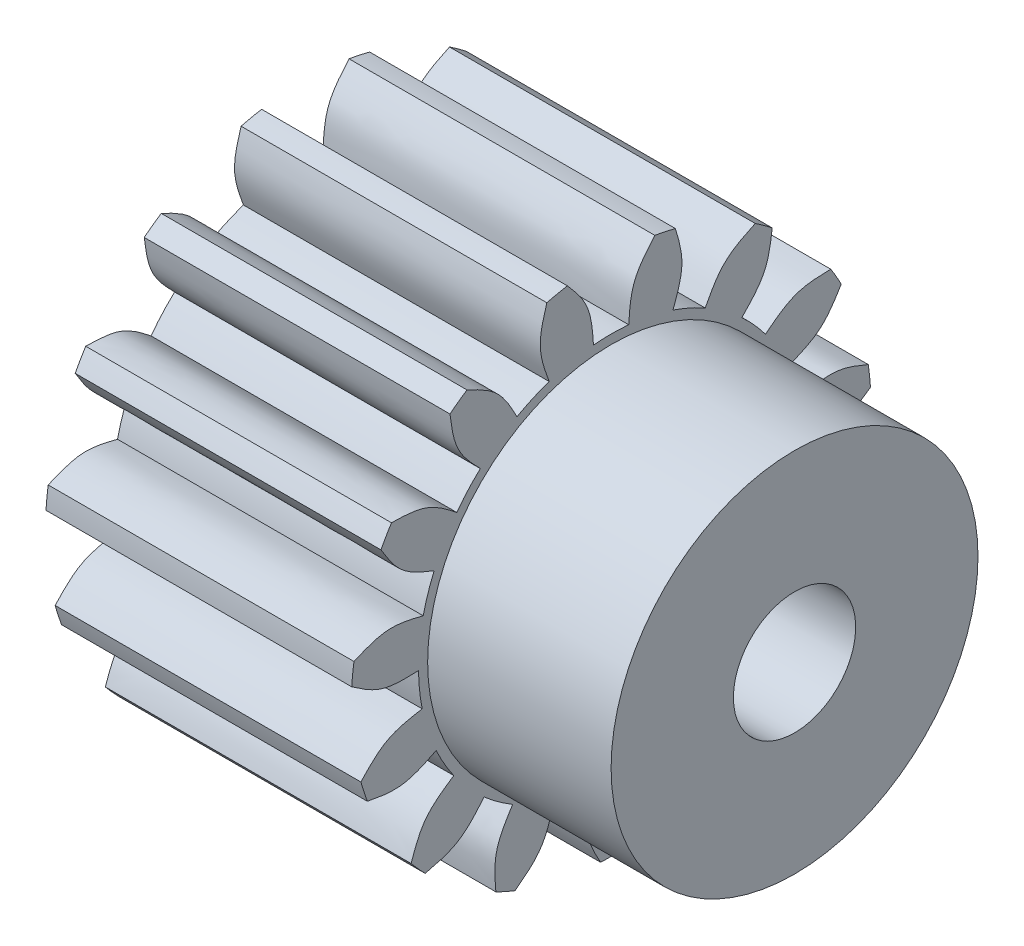
SolidWorks part; units mm, degrees
ref_plane "Front" through (0, 0, 0) normal (0, 0, 1) x (1, 0, 0)
ref_plane "Top" through (0, 0, 0) normal (0, 1, 0) x (1, 0, 0)
ref_plane "Right" through (0, 0, 0) normal (1, 0, 0) x (0, 0, -1)
sketch "Ritning 1" plane through (0, 0, 0) normal (0, 0, 1) x (1, 0, 0)
  line L0 (-20, -10.625) -> (20, -10.625) construction
  line L1 (-20, -5.625) -> (20, -5.625)
  line L2 (20, -5.625) -> (20, 4.375)
  line L3 (20, 4.375) -> (5, 4.375)
  line L4 (5, 4.375) -> (5, 10.625)
  line L5 (5, 10.625) -> (-20, 10.625)
  line L6 (-20, 10.625) -> (-20, -5.625)
  line L7 (-20, -5.625) -> (-20, -10.625) construction
  line L8 (20, -10.625) -> (20, -5.625) construction
  line L9 (-20, -10.625) -> (-5, -10.625) construction
  dimension "D1" = 5
  dimension "D2" = 20
  dimension "D3" = 20
  dimension "D4" = 4.375
  dimension "D5" = 10.625
  dimension "D6" = 5.625
revolve "Kugghjulsämne" add sketch "Ritning 1" angle 360 about L0
sketch "Ritning 2" plane through (-20, 0, 0) normal (-1, 0, 0) x (0, 0, 1)
  line L0 (0, -10.625) -> (0, 10.625) construction
  line L1 (3.5742, 10.3223) -> (0, 13.8965)
  line L2 (-3.5742, 10.3223) -> (0, 13.8965)
  line L3 (0, -10.625) -> (3.5742, -10.625) construction
  arc A0 (1.441, 5.0589) -> (-1.441, 5.0589) centre (0, -10.625) ccw
  circle A1 centre (0, -10.625) radius 21.25 construction
  spline S0 degree 3 poles (3.5742, 10.3223) (2.9469, 9.5929) (1.6476, 8.0821) (1.5115, 6.0896) (1.441, 5.0589) knots 0 0 0 0 0.482768 1 1 1 1
  spline S1 degree 3 poles (-3.5742, 10.3223) (-2.9469, 9.5929) (-1.6476, 8.0821) (-1.5115, 6.0896) (-1.441, 5.0589) knots 0 0 0 0 0.482768 1 1 1 1
  dimension "D1" = 15.75
  dimension "D2" = 1.441
  dimension "D3" = 1.9635
  dimension "D4" = 3.5742
  dimension "D5" = 18.6469
  dimension "D6" = 1.9635
  dimension "D7" = 20.9473
extrude "Kugglucka" cut sketch "Ritning 2" against normal up to surface (25 mm away) up to face at (5, -10.625, 21.25)
pattern_circular "CirPattern" count 15 over 360 about axis through (-20, -10.625, 0) along (-1, 0, 0) of "Kugglucka"
